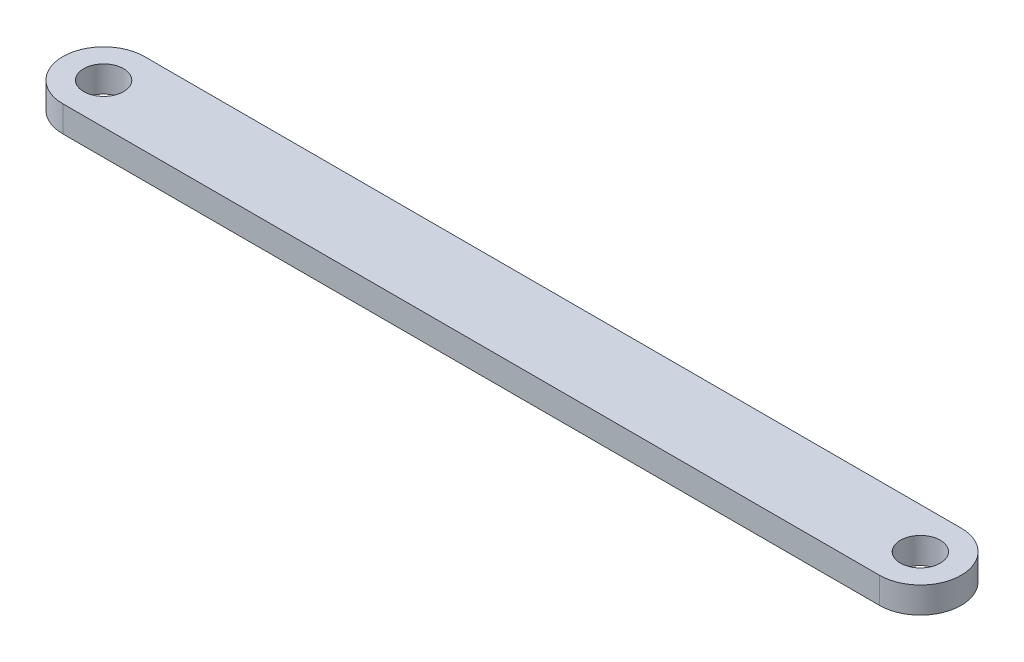
SolidWorks part; units mm, degrees
ref_plane "前视基准面" through (0, 0, 0) normal (0, 0, 1) x (1, 0, 0)
ref_plane "上视基准面" through (0, 0, 0) normal (0, 1, 0) x (1, 0, 0)
ref_plane "右视基准面" through (0, 0, 0) normal (1, 0, 0) x (0, 0, -1)
sketch "草图1" plane through (0, 0, 0) normal (0, 1, 0) x (1, 0, 0)
  line L0 (0, 0) -> (250, 0) construction
  line L1 (0, 12.5) -> (250, 12.5)
  line L2 (0, -12.5) -> (250, -12.5)
  arc A0 (0, 12.5) -> (0, -12.5) centre (0, 0) ccw
  arc A1 (250, -12.5) -> (250, 12.5) centre (250, 0) ccw
  circle A2 centre (0, 0) radius 6.1
  circle A3 centre (250, 0) radius 6.1
  point P3 (125, 0)
  dimension "D2" = 12.2
  dimension "D4" = 12.2
  dimension "D1" = 250
  dimension "D3" = 25
extrude "凸台-拉伸1" add sketch "草图1" along normal blind 8
